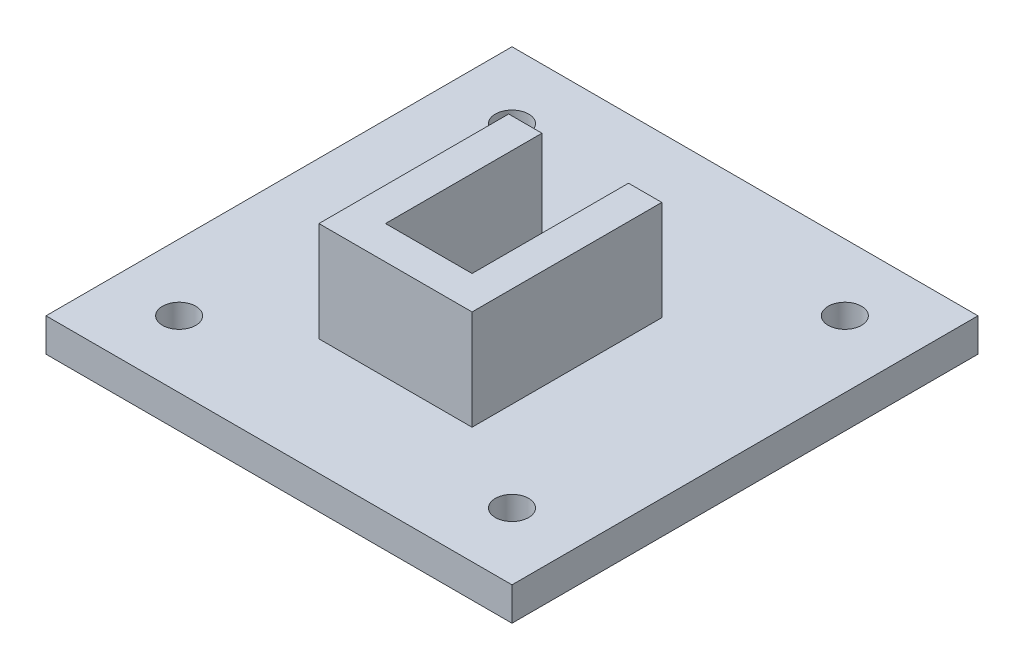
SolidWorks part; units mm, degrees
material "Chromium Copper, UNS C18200"
ref_plane "前视基准面" through (0, 0, 0) normal (0, 0, 1) x (1, 0, 0)
ref_plane "上视基准面" through (0, 0, 0) normal (0, 1, 0) x (1, 0, 0)
ref_plane "右视基准面" through (0, 0, 0) normal (1, 0, 0) x (0, 0, -1)
sketch "Sketch1" plane through (0, 0, 0) normal (0, 1, 0) x (1, 0, 0)
  line L1 (-35, 35) -> (35, 35)
  line L2 (-35, 35) -> (-35, -35)
  line L3 (-35, -35) -> (35, -35)
  line L4 (35, 35) -> (35, -35)
  line L5 (-35, 35) -> (35, -35) construction
  line L6 (-35, -35) -> (35, 35) construction
  point P0 (0, 0)
extrude "Boss-Extrude1" add sketch "Sketch1" along normal blind 5
sketch "Sketch2" plane through (0, 5, 0) normal (0, 1, 0) x (1, 0, 0)
  circle A0 centre (-25, 25) radius 2.5
extrude "Cut-Extrude1" cut sketch "Sketch2" against normal blind 5
sketch "Sketch3" plane through (0, 5, 0) normal (0, 1, 0) x (1, 0, 0)
  circle A0 centre (25, 25) radius 2.5
extrude "Cut-Extrude2" cut sketch "Sketch3" against normal blind 5
sketch "Sketch4" plane through (0, 5, 0) normal (0, 1, 0) x (1, 0, 0)
  circle A0 centre (-25, -25) radius 2.5
extrude "Cut-Extrude3" cut sketch "Sketch4" against normal blind 5
sketch "Sketch5" plane through (0, 5, 0) normal (0, 1, 0) x (1, 0, 0)
  circle A0 centre (25, -25) radius 2.5
extrude "Cut-Extrude4" cut sketch "Sketch5" against normal blind 5
sketch "Sketch6" plane through (0, 5, 0) normal (0, 1, 0) x (1, 0, 0)
  line L1 (-11.5, 17.5) -> (11.5, 17.5)
  line L2 (-11.5, 17.5) -> (-11.5, -17.5)
  line L3 (-11.5, -17.5) -> (11.5, -17.5)
  line L4 (11.5, 17.5) -> (11.5, -17.5)
  line L5 (-11.5, 17.5) -> (11.5, -17.5) construction
  line L6 (-11.5, -17.5) -> (11.5, 17.5) construction
  point P0 (0, 0)
extrude "Boss-Extrude2" add sketch "Sketch6" along normal blind 15
sketch "Sketch7" plane through (0, 20, 0) normal (0, 1, 0) x (1, 0, 0)
  line L1 (-6.5, 17.5) -> (6.5, 17.5)
  line L2 (-6.5, 17.5) -> (-6.5, -12.5)
  line L3 (-6.5, -12.5) -> (6.5, -12.5)
  line L4 (6.5, 17.5) -> (6.5, -12.5)
  line L5 (-6.5, 17.5) -> (6.5, -12.5) construction
  line L6 (-6.5, -12.5) -> (6.5, 17.5) construction
  point P0 (0, 2.5)
extrude "Cut-Extrude5" cut sketch "Sketch7" against normal blind 15
sketch "Sketch8" plane through (0, 20, 0) normal (0, 1, 0) x (1, 0, 0)
  line L0 (-11.5, 17.5) -> (-11.5, -17.5) construction
  line L1 (-11.5, 17.5) -> (-6.5, 17.5)
  line L2 (-11.5, 17.5) -> (-11.5, 11)
  line L3 (-11.5, 11) -> (-6.5, 11)
  line L4 (-6.5, 17.5) -> (-6.5, 11)
  line L5 (-6.5, 17.5) -> (-6.5, -12.5) construction
extrude "Cut-Extrude6" cut sketch "Sketch8" against normal blind 15
sketch "Sketch9" plane through (0, 20, 0) normal (0, 1, 0) x (1, 0, 0)
  line L0 (11.5, -17.5) -> (11.5, 17.5) construction
  line L1 (6.5, 17.5) -> (11.5, 17.5)
  line L2 (6.5, 17.5) -> (6.5, 11)
  line L3 (6.5, 11) -> (11.5, 11)
  line L4 (11.5, 17.5) -> (11.5, 11)
extrude "Cut-Extrude7" cut sketch "Sketch9" against normal blind 15
